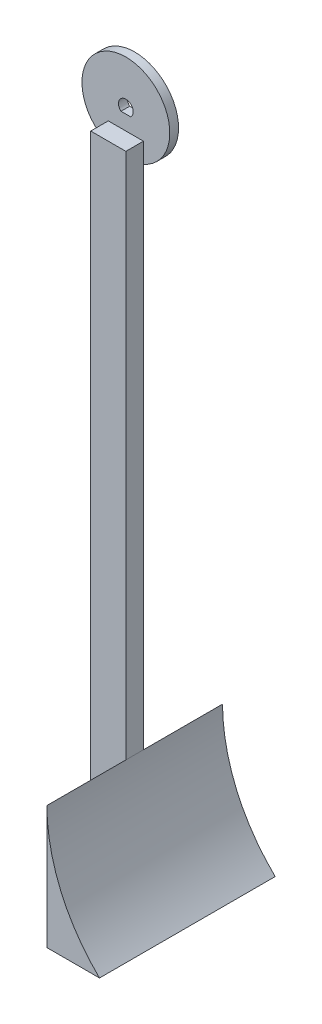
SolidWorks part; units mm, degrees
ref_plane "Front Plane" through (0, 0, 0) normal (0, 0, 1) x (1, 0, 0)
ref_plane "Top Plane" through (0, 0, 0) normal (0, 1, 0) x (1, 0, 0)
ref_plane "Right Plane" through (0, 0, 0) normal (1, 0, 0) x (0, 0, -1)
sketch "Sketch2" plane through (0, 0, 0) normal (0, 0, 1) x (1, 0, 0)
  line L0 (0, 2.1) -> (0, -1.575)
  line L1 (0, -13.75) -> (0, 13.75) construction
  line L2 (0, -1.575) -> (1.389, -1.575)
  line L3 (0, -1.575) -> (-1.389, -1.575)
  circle A0 centre (0, 0) radius 12.5
  arc A1 (1.389, -1.575) -> (-1.389, -1.575) centre (0, 0) ccw
  dimension "D1" = 4.2
extrude "Boss-Extrude1" add sketch "Sketch2" along normal blind 2.5 contours A0 A1 L2 L3
ref_plane "Plane1" through (0, 0, 2.5) normal (0, 0, 1) x (1, 0, 0)
sketch "Sketch4" plane through (0, 0, 2.5) normal (0, 0, 1) x (1, 0, 0)
  line L0 (-5, -165.7544) -> (5, -165.7544)
  line L1 (0, -13.75) -> (0, 13.75) construction
  line L2 (0, -5) -> (0, -5.7544)
  line L3 (0, -5.7544) -> (5, -5.7544)
  line L4 (0, -5.7544) -> (-5, -5.7544)
  line L5 (-5, -5.7544) -> (-5, -165.7544)
  line L6 (5, -165.7544) -> (5, -5.7544)
  line L7 (-5, -165.7544) -> (-5, -190.7544)
  line L8 (-5, -190.7544) -> (5, -190.7544)
extrude "Boss-Extrude2" add sketch "Sketch4" along normal blind 5 contours L0 L6 L3 L4 L5
ref_plane "Plane2" through (5, 0, 0) normal (1, 0, 0) x (0, 0, -1)
sketch "Sketch5" plane through (5, 0, 0) normal (1, 0, 0) x (0, 0, -1)
  line L0 (-5, -165.7544) -> (-5, -155.7544)
  line L1 (-7.5, -165.7544) -> (-2.5, -165.7544) construction
  line L2 (-5, -155.7544) -> (20, -155.7544)
  line L3 (-5, -155.7544) -> (-30, -155.7544)
  line L4 (20, -155.7544) -> (20, -190.7544)
  line L5 (-30, -155.7544) -> (-30, -190.7544)
  line L8 (-5, -190.7544) -> (-30, -190.7544)
  line L9 (-5, -190.7544) -> (20, -190.7544)
extrude "Boss-Extrude3" add sketch "Sketch5" along normal blind 15
ref_plane "Plane4" through (-5, 0, 0) normal (-1, 0, 0) x (0, 0, 1)
sketch "Sketch9" plane through (-5, 0, 0) normal (-1, 0, 0) x (0, 0, 1)
  line L0 (7.5, -165.7544) -> (7.5, -190.7544)
  line L1 (2.5, -165.7544) -> (7.5, -165.7544)
  line L2 (2.5, -165.7544) -> (2.5, -190.7544)
  line L3 (-20, -190.7544) -> (30, -190.7544) construction
  line L4 (2.5, -190.7544) -> (7.5, -190.7544)
extrude "Boss-Extrude4" add sketch "Sketch9" against normal blind 10
ref_plane "Plane3" through (0, 0, -20) normal (0, 0, -1) x (-1, 0, 0)
sketch "Sketch6" plane through (0, 0, -20) normal (0, 0, -1) x (-1, 0, 0)
  line L0 (-5, -155.7544) -> (-20, -155.7544)
  line L1 (-20, -155.7544) -> (-20, -190.7544)
  arc A0 (-5, -155.7544) -> (-20, -190.7544) centre (-54.0319, -155.455) cw
extrude "Cut-Extrude1" cut sketch "Sketch6" against normal blind 142
sketch "Sketch10" plane through (-5, 0, 0) normal (-1, 0, 0) x (0, 0, 1)
  line L0 (5, -190.7544) -> (5, -155.0559)
  line L1 (2.5, -190.7544) -> (7.5, -190.7544) construction
  line L2 (5, -155.0559) -> (2.5, -155.0559)
  line L3 (5, -190.7544) -> (5, -163.2544)
  line L4 (2.5, -11.4564) -> (2.5, -190.7544) construction
  line L5 (2.5, -155.0559) -> (7.7769, -155.0559)
